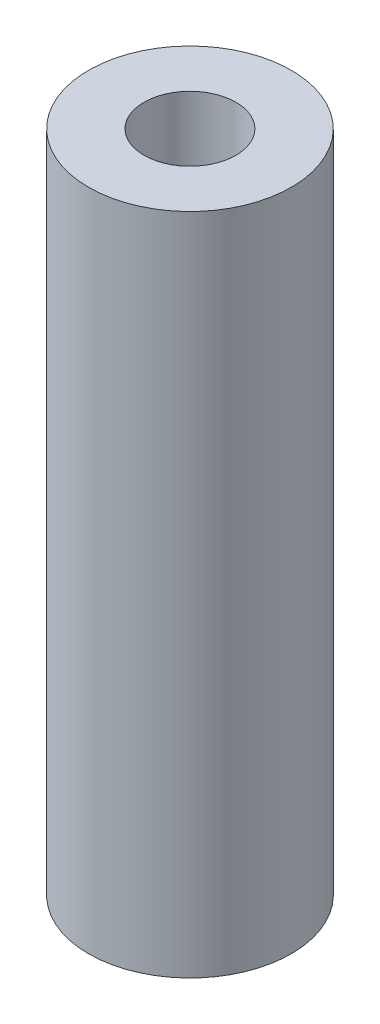
SolidWorks part; units mm, degrees
ref_plane "Front Plane" through (0, 0, 0) normal (0, 0, 1) x (1, 0, 0)
ref_plane "Top Plane" through (0, 0, 0) normal (0, 1, 0) x (1, 0, 0)
ref_plane "Right Plane" through (0, 0, 0) normal (1, 0, 0) x (0, 0, -1)
sketch "Sketch1" plane through (0, 0, 0) normal (0, 1, 0) x (1, 0, 0)
  circle A0 centre (0, 0) radius 5.955
  dimension "D1" = 11.91
extrude "Boss-Extrude1" add sketch "Sketch1" along normal blind 39
sketch "Sketch2" plane through (0, 39, 0) normal (0, 1, 0) x (1, 0, 0)
  circle A0 centre (0, 0) radius 2.7
  dimension "D1" = 5.4
extrude "Cut-Extrude1" cut sketch "Sketch2" against normal blind 4.5
